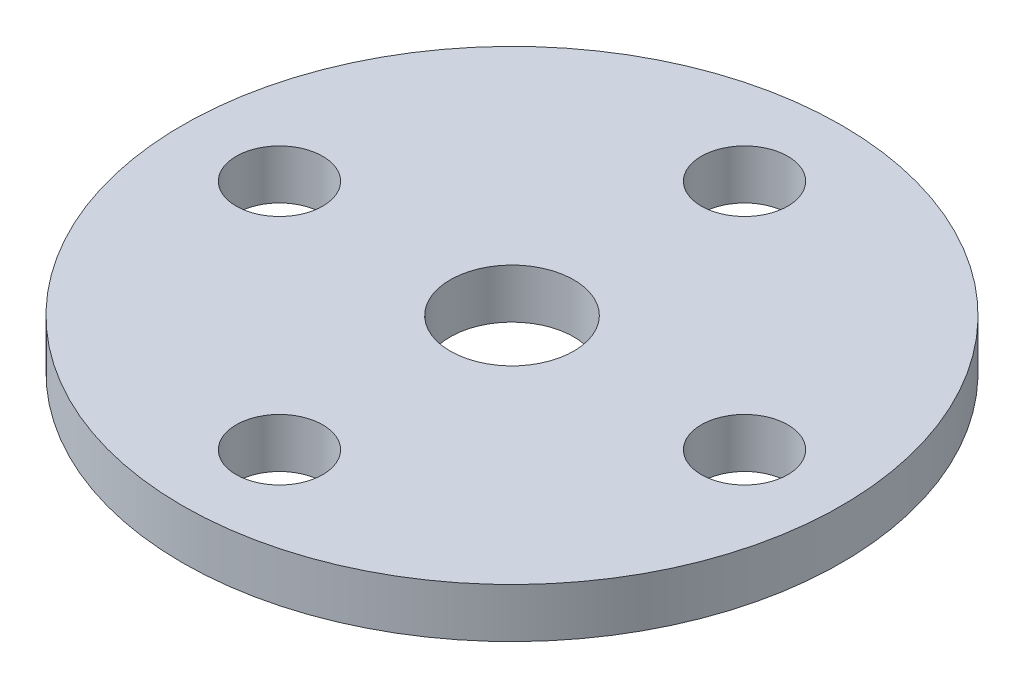
SolidWorks part; units mm, degrees
ref_plane "前基準面" through (0, 0, 0) normal (0, 0, 1) x (1, 0, 0)
ref_plane "上基準面" through (0, 0, 0) normal (0, 1, 0) x (1, 0, 0)
ref_plane "右基準面" through (0, 0, 0) normal (1, 0, 0) x (0, 0, -1)
sketch "草圖1" plane through (0, 0, 0) normal (0, 1, 0) x (1, 0, 0)
  circle A0 centre (0, 0) radius 16
  dimension "D1" = 32
extrude "填料-伸長1" add sketch "草圖1" along normal blind 2.4
sketch "草圖2" plane through (0, 2.4, 0) normal (0, 1, 0) x (1, 0, 0)
  circle A0 centre (0, 0) radius 3
  dimension "D1" = 6
sketch "草圖4" plane through (0, 2.4, 0) normal (0, 1, 0) x (1, 0, 0)
  circle A0 centre (0, 11.29) radius 2.1
  circle A1 centre (11.29, 0) radius 2.1
  circle A2 centre (0, -11.29) radius 2.1
  circle A3 centre (-11.29, 0) radius 2.1
  point P12 (0, 0)
  dimension "D1" = 4.2
  dimension "D2" = 11.29
  dimension "D3" = 4
extrude "除料-伸長2" cut sketch "草圖4" against normal up to next
extrude "除料-伸長3" cut sketch "草圖2" against normal up to next
